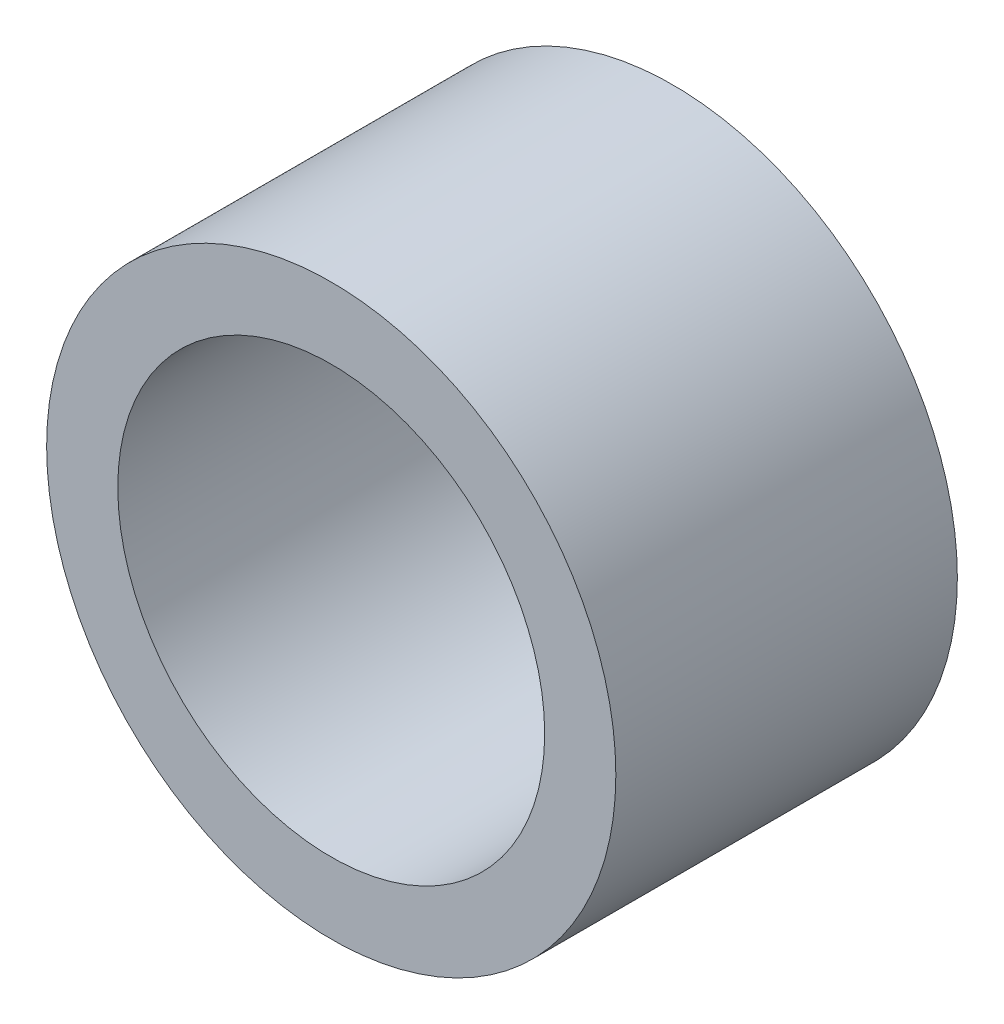
SolidWorks part; units mm, degrees
ref_plane "Plan de face" through (0, 0, 0) normal (0, 0, 1) x (1, 0, 0)
ref_plane "Plan de dessus" through (0, 0, 0) normal (0, 1, 0) x (1, 0, 0)
ref_plane "Plan de droite" through (0, 0, 0) normal (1, 0, 0) x (0, 0, -1)
sketch "Esquisse1" plane through (0, 0, 0) normal (0, 0, 1) x (1, 0, 0)
  circle A0 centre (0, 0) radius 10
  circle A1 centre (0, 0) radius 7.5
  dimension "D1" = 20
  dimension "D2" = 15
extrude "Boss.-Extru.1" add sketch "Esquisse1" along normal blind 12
equation "\"è.2\"=14.4"
